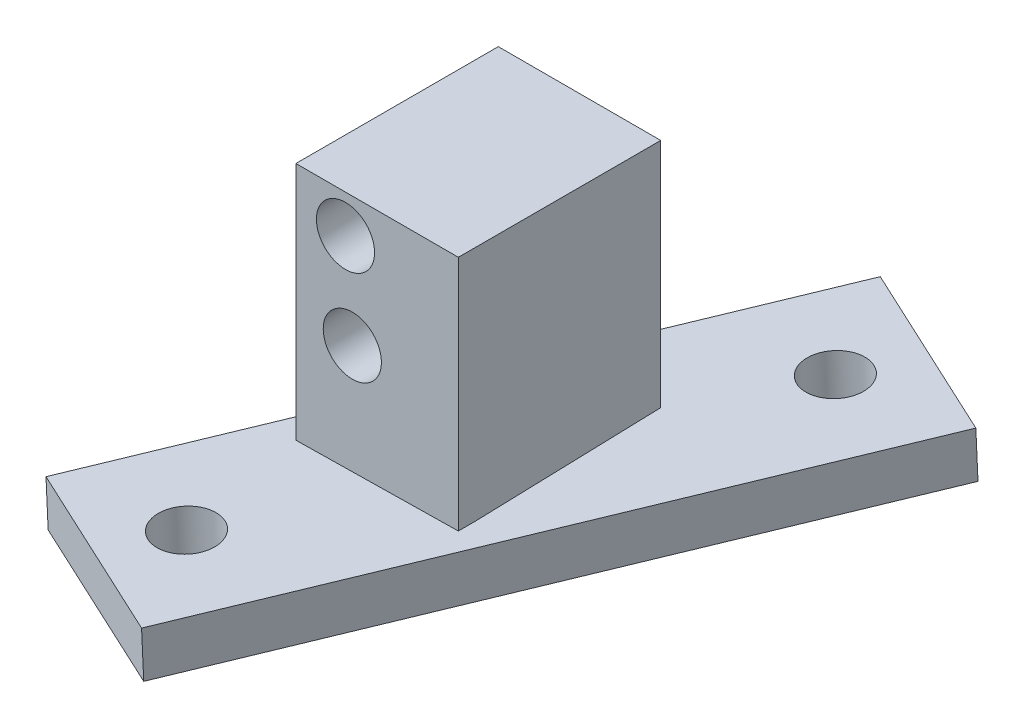
SolidWorks part; units mm, degrees
ref_plane "Front Plane" through (0, 0, 0) normal (0, 0, 1) x (1, 0, 0)
ref_plane "Top Plane" through (0, 0, 0) normal (0, 1, 0) x (1, 0, 0)
ref_plane "Right Plane" through (0, 0, 0) normal (1, 0, 0) x (0, 0, -1)
sketch "Sketch1" plane through (0, 0, 0) normal (0, 0, 1) x (1, 0, 0)
  line L0 (-191.7877, 237.82) -> (-174.0496, 237.82)
  line L1 (-195.4178, 237.5271) -> (-180.5722, 238.7251) construction
  line L2 (-174.0496, 237.82) -> (-174.0496, 212.2138)
  line L3 (-174.0496, 212.2138) -> (-191.7877, 212.2138)
  line L4 (-191.7877, 212.2138) -> (-191.7877, 237.82)
  line L5 (-193.9862, 215.2944) -> (-184.9478, 216.0238) construction
  line L6 (-193.9862, 215.2944) -> (-184.9478, 216.0238)
  arc A0 (-184.9478, 216.0238) -> (-180.3996, 218.0472) centre (-185.6285, 223.6772) ccw construction
  arc A1 (-184.9478, 216.0238) -> (-180.3996, 218.0472) centre (-185.6285, 223.6772) ccw
  circle A2 centre (-185.6285, 223.6772) radius 3.175
  circle A3 centre (-186.3724, 233.6772) radius 3.175
  dimension "D1" = 3.81
  dimension "D2" = 6.35
extrude "Boss-Extrude1" add sketch "Sketch1" along normal up to surface (22.098 mm away)
ref_plane "Plane1" through (-3.3933, 215.0438, 6.5402) normal (-0.0158, 0.9994, 0.0304) x (0.9999, 0.0158, 0.0005)
sketch "Sketch2" plane through (-3.3933, 215.0438, 6.5402) normal (-0.0158, 0.9994, 0.0304) x (0.9999, 0.0158, 0.0005)
  line L0 (-199.338, -32.0344) -> (-170.3548, 30.1202)
  line L1 (-170.3548, 30.1202) -> (-150.7876, 20.9958)
  line L2 (-150.7876, 20.9958) -> (-179.7708, -41.1587)
  line L3 (-179.7708, -41.1587) -> (-199.338, -32.0344)
  line L4 (-188.4081, -15.6366) -> (-170.6722, -15.6366) construction
  circle A0 centre (-186.334, -29.6905) radius 3.175
  circle A1 centre (-163.7916, 18.6519) radius 3.175
  dimension "D6" = 10.795
  dimension "D8" = 6.35
  dimension "D9" = 6.35
  dimension "D1" = 68.58
  dimension "D2" = 21.59
  dimension "D3" = 2.54
  dimension "D4" = 115
  dimension "D5" = 21.59
  dimension "D7" = 7.62
  dimension "D10" = 7.62
  dimension "D11" = 10.795
extrude "Boss-Extrude2" add sketch "Sketch2" against normal blind 5.08 contours L3 L0 L1 L2
sketch "Sketch3" plane through (0, 0, 22.098) normal (0, 0, 1) x (1, 0, 0)
  line L0 (-191.7877, 212.2138) -> (-191.7877, 211.6523)
  line L1 (-191.7877, 211.6523) -> (-174.0496, 211.9331)
  line L2 (-174.0496, 211.9331) -> (-174.0496, 212.2138)
  line L3 (-174.0496, 212.2138) -> (-191.7877, 212.2138)
extrude "Boss-Extrude3" add sketch "Sketch3" against normal up to surface (22.098 mm away) up to face at (-183.1974, 233.6772, 0)
